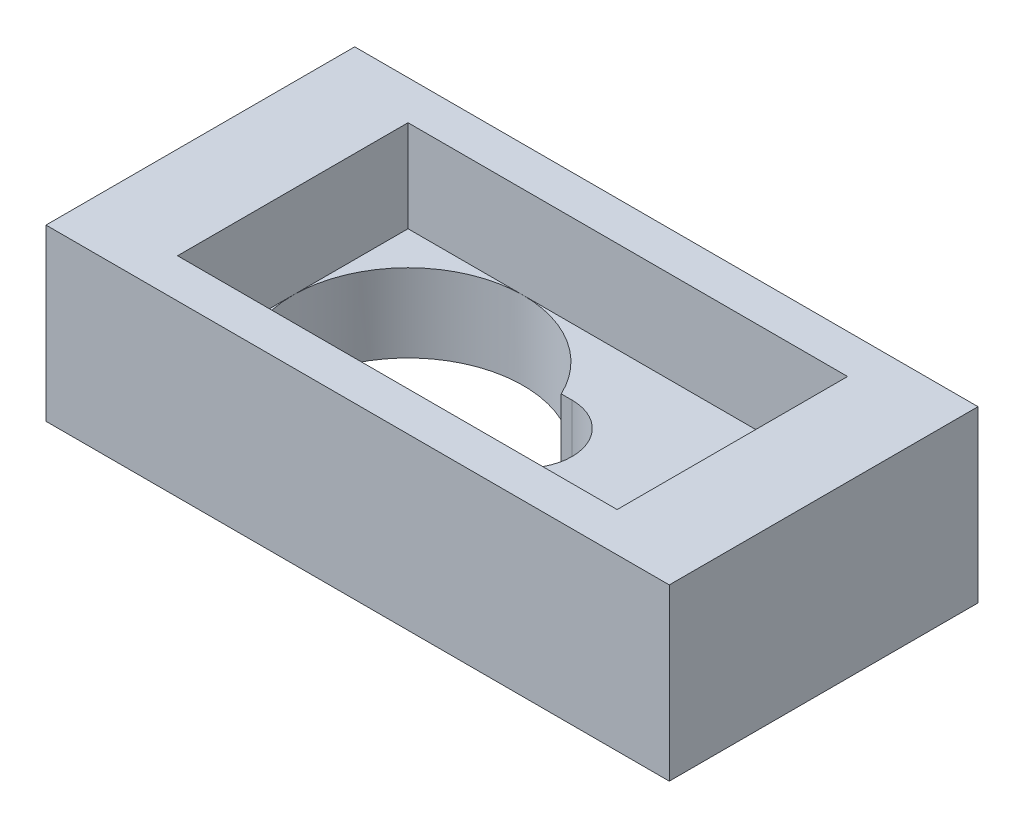
SolidWorks part; units mm, degrees
ref_plane "Front Plane" through (0, 0, 0) normal (0, 0, 1) x (1, 0, 0)
ref_plane "Top Plane" through (0, 0, 0) normal (0, 1, 0) x (1, 0, 0)
ref_plane "Right Plane" through (0, 0, 0) normal (1, 0, 0) x (0, 0, -1)
sketch "Sketch1" plane through (0, 0, 0) normal (0, 1, 0) x (1, 0, 0)
  line L0 (-0.9983, -2.6014) -> (-1.5544, -2.6014)
  line L5 (-0.9983, 2.3986) -> (-1.5544, 2.3986)
  line L10 (-17.5212, 5.7961) -> (-17.5212, -6.0039)
  line L14 (14.3788, 5.7961) -> (14.3788, -6.0039)
  line L16 (-17.5212, 5.7961) -> (-17.5212, 7.7961)
  line L17 (-17.5212, 7.7961) -> (14.3788, 7.7961)
  line L18 (14.3788, 5.7961) -> (14.3788, 7.7961)
  line L20 (-17.5212, -6.0039) -> (-17.5212, -8.0039)
  line L21 (-17.5212, -8.0039) -> (14.3788, -8.0039)
  line L22 (14.3788, -6.0039) -> (14.3788, -8.0039)
  arc A0 (-1.5544, 2.3986) -> (-1.5544, -2.6014) centre (-6.8957, -0.1014) ccw
  arc A1 (-0.9983, -2.6014) -> (-0.9983, 2.3986) centre (-0.9983, -0.1014) ccw
  dimension "D3" = 5
  dimension "D6" = 2
  dimension "D7" = 2
extrude "Boss-Extrude5" add sketch "Sketch1" along normal blind 4
sketch "Sketch8" plane through (0, 4, 0) normal (0, 1, 0) x (1, 0, 0)
  line L0 (-6.8957, 5.7961) -> (-12.7932, 5.7961)
  line L1 (-12.7932, 5.7961) -> (-12.7932, -0.1014)
  line L2 (-12.7932, -0.1014) -> (-12.7932, -5.9988)
  line L3 (-12.7932, -5.9988) -> (-6.8957, -5.9988)
  line L4 (-6.8957, -5.9988) -> (9.7043, -5.9988)
  line L5 (9.7043, -5.9988) -> (9.7043, 5.7961)
  line L6 (9.7043, 5.7961) -> (-6.8957, 5.7961)
  line L12 (-17.5212, 7.7961) -> (14.3788, 7.7961)
  line L13 (-17.5212, 7.7961) -> (-17.5212, -8.0039)
  line L14 (-17.5212, -8.0039) -> (14.3788, -8.0039)
  line L15 (14.3788, 7.7961) -> (14.3788, -8.0039)
  arc A0 (-1.5544, 2.3986) -> (-1.5544, -2.6014) centre (-6.8957, -0.1014) ccw construction
extrude "Boss-Extrude8" add sketch "Sketch8" along normal blind 4.7
